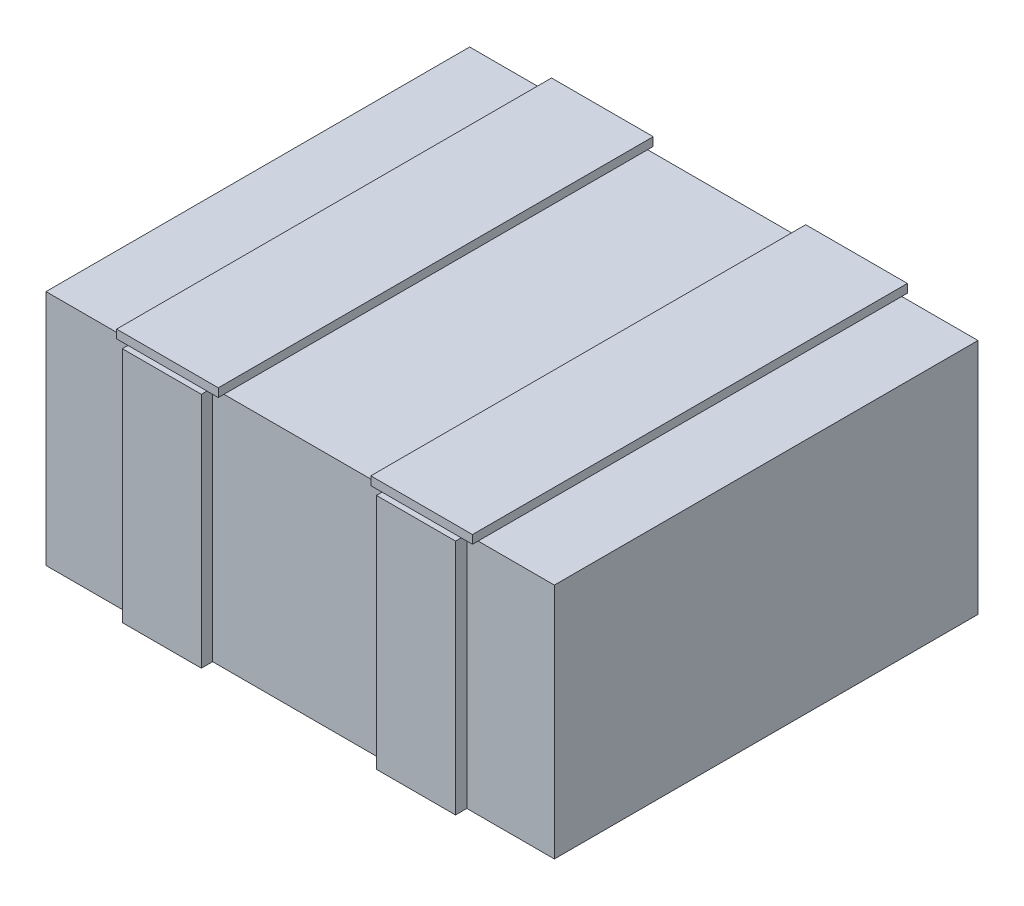
SolidWorks part; units mm, degrees
ref_plane "Front Plane" through (0, 0, 0) normal (0, 0, 1) x (1, 0, 0)
ref_plane "Top Plane" through (0, 0, 0) normal (0, 1, 0) x (1, 0, 0)
ref_plane "Right Plane" through (0, 0, 0) normal (1, 0, 0) x (0, 0, -1)
sketch "SK_P01_Pack" plane through (0, 0, 0) normal (0, 1, 0) x (1, 0, 0)
  line L0 (-45, -37.5) -> (45, -37.5)
  line L1 (45, -37.5) -> (45, 37.5)
  line L2 (45, 37.5) -> (-45, 37.5)
  line L3 (-45, 37.5) -> (-45, -37.5)
extrude "P01_Pack" add sketch "SK_P01_Pack" along normal blind 42
sketch "SK_P02_Strap" plane through (0, 0, 0) normal (0, 1, 0) x (1, 0, 0)
  line L0 (-31.5, -38.5) -> (-13.5, -38.5)
  line L1 (-13.5, -38.5) -> (-13.5, 38.5)
  line L2 (-13.5, 38.5) -> (-31.5, 38.5)
  line L3 (-31.5, 38.5) -> (-31.5, -38.5)
extrude "P02_Strap" add sketch "SK_P02_Strap" along normal blind 1.5 from offset 42
sketch "SK_P03_Strap" plane through (0, 0, 0) normal (0, 1, 0) x (1, 0, 0)
  line L0 (13.5, -38.5) -> (31.5, -38.5)
  line L1 (31.5, -38.5) -> (31.5, 38.5)
  line L2 (31.5, 38.5) -> (13.5, 38.5)
  line L3 (13.5, 38.5) -> (13.5, -38.5)
extrude "P03_Strap" add sketch "SK_P03_Strap" along normal blind 1.5 from offset 42
sketch "SK_P04_Strap" plane through (0, 0, 0) normal (0, 1, 0) x (1, 0, 0)
  line L0 (-29.5, 37.5) -> (-15.5, 37.5)
  line L1 (-15.5, 37.5) -> (-15.5, 39.5)
  line L2 (-15.5, 39.5) -> (-29.5, 39.5)
  line L3 (-29.5, 39.5) -> (-29.5, 37.5)
extrude "P04_Strap" add sketch "SK_P04_Strap" along normal blind 42
sketch "SK_P05_Strap" plane through (0, 0, 0) normal (0, 1, 0) x (1, 0, 0)
  line L0 (-29.5, -39.5) -> (-15.5, -39.5)
  line L1 (-15.5, -39.5) -> (-15.5, -37.5)
  line L2 (-15.5, -37.5) -> (-29.5, -37.5)
  line L3 (-29.5, -37.5) -> (-29.5, -39.5)
extrude "P05_Strap" add sketch "SK_P05_Strap" along normal blind 42
sketch "SK_P06_Strap" plane through (0, 0, 0) normal (0, 1, 0) x (1, 0, 0)
  line L0 (15.5, 37.5) -> (29.5, 37.5)
  line L1 (29.5, 37.5) -> (29.5, 39.5)
  line L2 (29.5, 39.5) -> (15.5, 39.5)
  line L3 (15.5, 39.5) -> (15.5, 37.5)
extrude "P06_Strap" add sketch "SK_P06_Strap" along normal blind 42
sketch "SK_P07_Strap" plane through (0, 0, 0) normal (0, 1, 0) x (1, 0, 0)
  line L0 (15.5, -39.5) -> (29.5, -39.5)
  line L1 (29.5, -39.5) -> (29.5, -37.5)
  line L2 (29.5, -37.5) -> (15.5, -37.5)
  line L3 (15.5, -37.5) -> (15.5, -39.5)
extrude "P07_Strap" add sketch "SK_P07_Strap" along normal blind 42
